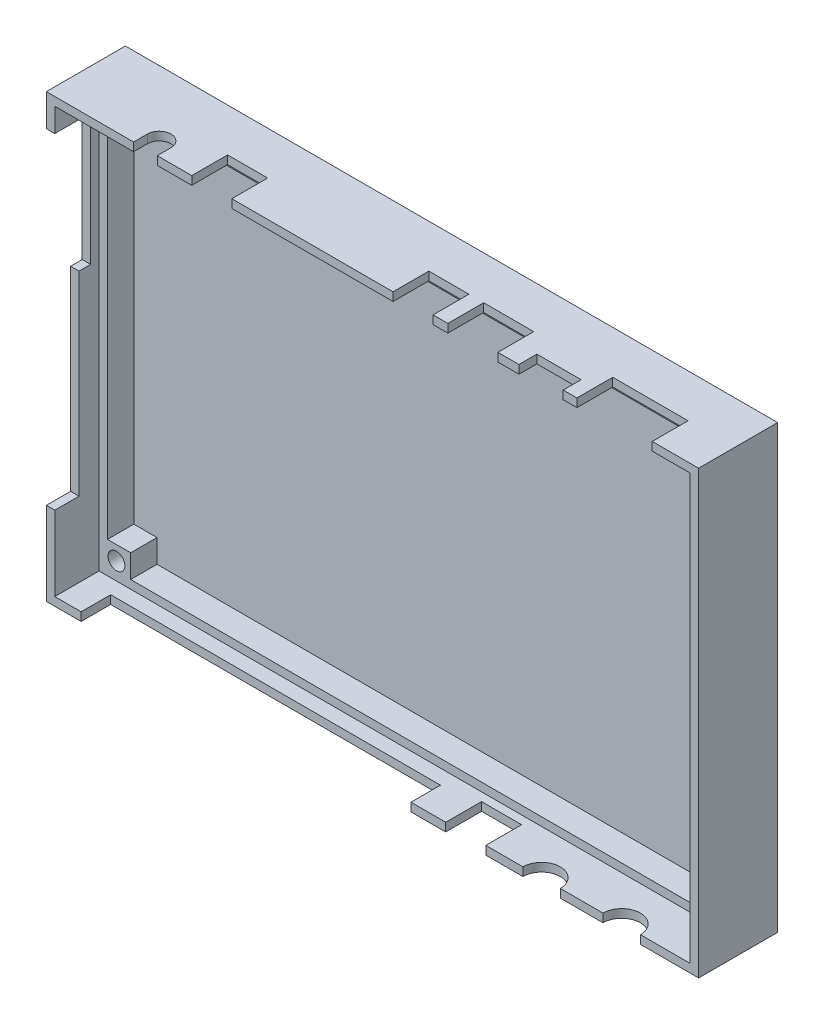
SolidWorks part; units mm, degrees
ref_plane "Front Plane" through (0, 0, 0) normal (0, 0, 1) x (1, 0, 0)
ref_plane "Top Plane" through (0, 0, 0) normal (0, 1, 0) x (1, 0, 0)
ref_plane "Right Plane" through (0, 0, 0) normal (1, 0, 0) x (0, 0, -1)
sketch "Sketch1" plane through (0, 0, 0) normal (0, 0, 1) x (1, 0, 0)
  line L1 (-60.3, 40.3) -> (60.3, 40.3)
  line L2 (-60.3, 40.3) -> (-60.3, -40.3)
  line L3 (-60.3, -40.3) -> (60.3, -40.3)
  line L4 (60.3, 40.3) -> (60.3, -40.3)
  line L5 (-60.3, 40.3) -> (60.3, -40.3) construction
  line L6 (-60.3, -40.3) -> (60.3, 40.3) construction
  point P0 (0, 0)
  dimension "D1" = 80.6
  dimension "D2" = 120.6
extrude "Boss-Extrude1" add sketch "Sketch1" along normal blind 1.6
sketch "Sketch2" plane through (0, 0, 0) normal (0, 0, 1) x (1, 0, 0)
  line L0 (-60.3, 40.3) -> (-60.3, -40.3)
  line L1 (-60.3, -40.3) -> (60.3, -40.3)
  line L2 (60.3, -40.3) -> (60.3, 40.3)
  line L3 (60.3, 40.3) -> (-60.3, 40.3)
  line L4 (-61.9, 41.9) -> (-61.9, -41.9)
  line L5 (-61.9, -41.9) -> (61.9, -41.9)
  line L6 (61.9, -41.9) -> (61.9, 41.9)
  line L7 (61.9, 41.9) -> (-61.9, 41.9)
  dimension "D1" = 1.6
  dimension "D2" = 1.6
  dimension "D3" = 1.6
  dimension "D4" = 1.6
  dimension "D5" = 83.8
  dimension "D6" = 123.8
extrude "Boss-Extrude2" add sketch "Sketch2" along normal blind 8.2
sketch "Sketch3" plane through (0, 0, 1.6) normal (0, 0, 1) x (1, 0, 0)
  line L0 (60.3, -40.3) -> (60.3, 40.3) construction
  line L3 (-58.7, 34.3) -> (-54.3, 34.3)
  line L4 (-54.3, 38.5) -> (-54.3, 34.3)
  line L6 (60.3, 40.3) -> (60.3, -40.3)
  line L7 (58.7, 34.3) -> (54.3, 34.3)
  line L8 (54.3, 38.5) -> (54.3, 34.3)
  line L9 (60.3, -40.3) -> (60.3, 40.3) construction
  line L10 (60.3, 40.3) -> (-60.3, 40.3)
  line L11 (60.3, -40.3) -> (-60.3, -40.3)
  line L13 (58.7, -34.3) -> (54.3, -34.3)
  line L14 (54.3, -38.7) -> (54.3, -34.3)
  line L16 (-60.3, -40.3) -> (-60.3, 40.3)
  line L17 (-58.7, -34.3) -> (-54.3, -34.3)
  line L18 (-54.3, -38.7) -> (-54.3, -34.3)
  line L19 (54.3, 38.5) -> (-54.3, 38.5)
  line L20 (58.7, 34.3) -> (58.7, -34.3)
  line L21 (54.3, -38.7) -> (-54.3, -38.7)
  line L22 (-58.7, -34.3) -> (-58.7, 34.3)
  line L23 (-60.3, -40.3) -> (60.3, -40.3) construction
  line L24 (-60.3, 40.3) -> (-60.3, -40.3) construction
  line L25 (60.3, 40.3) -> (-60.3, 40.3) construction
  line L26 (60.3, 40.3) -> (-60.3, 40.3) construction
  dimension "D1" = 6
  dimension "D2" = 6
  dimension "D3" = 6
  dimension "D4" = 6
  dimension "D6" = 1.6
  dimension "D7" = 1.6
  dimension "D8" = 1.6
extrude "Boss-Extrude3" add sketch "Sketch3" along normal blind 5
sketch "Sketch4" plane through (0, 0, 6.6) normal (0, 0, 1) x (1, 0, 0)
  circle A0 centre (-57, 37) radius 1.6
  circle A1 centre (57, 37) radius 1.6
  circle A2 centre (57, -37) radius 1.6
  circle A3 centre (-57, -37) radius 1.6
  dimension "D3" = 3.2
  dimension "D1" = 57
  dimension "D2" = 37
  dimension "D4" = 74
  dimension "D5" = 114
  dimension "D6" = 74
  dimension "D7" = 114
extrude "Cut-Extrude1" cut sketch "Sketch4" against normal blind 5
sketch "Sketch5" plane through (0, 0, 8.2) normal (0, 0, 1) x (1, 0, 0)
  line L0 (-60.3, -40.3) -> (60.3, -40.3) construction
  line L1 (61.9, -41.9) -> (21.5, -41.9)
  line L2 (61.9, -41.9) -> (61.9, -40.3)
  line L3 (61.9, -40.3) -> (21.5, -40.3)
  line L4 (21.5, -41.9) -> (21.5, -40.3)
  line L5 (-61.9, -41.9) -> (61.9, -41.9) construction
  line L6 (13.9, -40.3) -> (7.3, -40.3)
  line L7 (13.9, -40.3) -> (13.9, -41.9)
  line L8 (13.9, -41.9) -> (7.3, -41.9)
  line L9 (7.3, -40.3) -> (7.3, -41.9)
  dimension "D1" = 38.8
  dimension "D2" = 46.4
  dimension "D3" = 53
  dimension "D4" = 7.6
extrude "Boss-Extrude4" add sketch "Sketch5" along normal blind 6.8
sketch "Sketch6" plane through (0, -41.9, 0) normal (0, -1, 0) x (1, 0, 0)
  line L0 (21.5, 15) -> (61.9, 15) construction
  circle A0 centre (32.1, 15) radius 3.55
  circle A1 centre (47.3, 15) radius 3.55
  dimension "D1" = 7.1
  dimension "D2" = 15.2
  dimension "D3" = 14.6
extrude "Cut-Extrude2" cut sketch "Sketch6" against normal blind 6.8
sketch "Sketch7" plane through (0, 0, 8.2) normal (0, 0, 1) x (1, 0, 0)
  line L0 (-61.9, -26.1) -> (-61.9, -41.9)
  line L1 (-61.9, 41.9) -> (-61.9, -41.9) construction
  line L2 (-61.9, -41.9) -> (7.3, -41.9) construction
  line L3 (-61.9, -41.9) -> (-55.3, -41.9)
  line L4 (-55.3, -41.9) -> (-55.3, -40.3)
  line L5 (-60.3, -40.3) -> (7.3, -40.3) construction
  line L6 (-55.3, -40.3) -> (-60.3, -40.3)
  line L7 (-60.3, -40.3) -> (-60.3, -26.1)
  line L8 (-60.3, 40.3) -> (-60.3, -40.3) construction
  line L9 (-60.3, -26.1) -> (-61.9, -26.1)
  dimension "D1" = 5
  dimension "D2" = 14.2
extrude "Boss-Extrude5" add sketch "Sketch7" along normal blind 6.8
sketch "Sketch14" plane through (0, 0, 8.2) normal (0, 0, 1) x (1, 0, 0)
  line L1 (-55.3, -40.3) -> (7.3, -40.3)
  line L2 (-55.3, -40.3) -> (-55.3, -41.9)
  line L3 (-55.3, -41.9) -> (7.3, -41.9)
  line L4 (7.3, -40.3) -> (7.3, -41.9)
sketch "Sketch8" plane through (0, 0, 8.2) normal (0, 0, 1) x (1, 0, 0)
  line L0 (-60.3, 40.3) -> (-60.3, -26.1) construction
  line L1 (-61.9, -26.1) -> (-60.3, -26.1)
  line L2 (-61.9, -26.1) -> (-61.9, 10.9)
  line L3 (-61.9, 10.9) -> (-60.3, 10.9)
  line L4 (-60.3, -26.1) -> (-60.3, 10.9)
  dimension "D1" = 37
extrude "Boss-Extrude6" add sketch "Sketch8" along normal blind 2.2
sketch "Sketch9" plane through (0, 0, 8.2) normal (0, 0, 1) x (1, 0, 0)
  line L0 (-60.3, 35.8) -> (-61.9, 35.8)
  line L1 (-60.3, 40.3) -> (-60.3, -40.3) construction
  line L2 (-61.9, 41.9) -> (-61.9, 10.9) construction
  line L3 (-61.9, 35.8) -> (-61.9, 41.9)
  line L4 (-61.9, 41.9) -> (-34.3, 41.9)
  line L5 (61.9, 41.9) -> (-61.9, 41.9) construction
  line L6 (-34.3, 41.9) -> (-34.3, 40.3)
  line L7 (60.3, 40.3) -> (-60.3, 40.3) construction
  line L8 (-34.3, 40.3) -> (-60.3, 40.3)
  line L9 (-60.3, 40.3) -> (-60.3, 35.8)
  line L10 (-26.7, 41.9) -> (-26.7, 40.3)
  line L11 (60.3, 40.3) -> (-60.3, 40.3) construction
  line L12 (-26.7, 40.3) -> (3.9, 40.3)
  line L13 (3.9, 40.3) -> (3.9, 41.9)
  line L14 (3.9, 41.9) -> (-26.7, 41.9)
  line L16 (11.5, 41.9) -> (14.3, 41.9)
  line L17 (11.5, 41.9) -> (11.5, 40.3)
  line L18 (11.5, 40.3) -> (14.3, 40.3)
  line L19 (14.3, 41.9) -> (14.3, 40.3)
  dimension "D1" = 4.5
  dimension "D2" = 26
  dimension "D3" = 33.6
  dimension "D4" = 64.2
  dimension "D5" = 71.8
  dimension "D6" = 2.8
  dimension "D7" = 7.6
  dimension "D8" = 7.6
extrude "Boss-Extrude7" add sketch "Sketch9" along normal blind 6.8
sketch "Sketch10" plane through (0, 41.9, 0) normal (0, 1, 0) x (1, 0, 0)
  line L0 (-45.35, -12.4) -> (-45.35, -15)
  line L1 (-34.3, -15) -> (-61.9, -15) construction
  line L2 (-45.35, -15) -> (-40.85, -15)
  line L3 (-40.85, -15) -> (-40.85, -12.4)
  arc A0 (-40.85, -12.4) -> (-45.35, -12.4) centre (-43.1, -12.4) ccw
  dimension "D1" = 4.5
  dimension "D2" = 2.6
  dimension "D3" = 18.8
extrude "Cut-Extrude3" cut sketch "Sketch10" against normal blind 6.8
sketch "Sketch11" plane through (0, 0, 8.2) normal (0, 0, 1) x (1, 0, 0)
  line L0 (61.9, 41.9) -> (14.3, 41.9) construction
  line L1 (23.8, 41.9) -> (38.8, 41.9)
  line L2 (23.8, 41.9) -> (23.8, 40.3)
  line L3 (23.8, 40.3) -> (38.8, 40.3)
  line L4 (38.8, 41.9) -> (38.8, 40.3)
  line L5 (60.3, 40.3) -> (-60.3, 40.3) construction
  dimension "D1" = 21.5
  dimension "D2" = 36.5
extrude "Boss-Extrude8" add sketch "Sketch11" along normal blind 6.8
sketch "Sketch12" plane through (0, 41.9, 0) normal (0, 1, 0) x (1, 0, 0)
  line L0 (38.8, -15) -> (23.8, -15) construction
  line L1 (27.8, -15) -> (36.2, -15)
  line L2 (27.8, -15) -> (27.8, -11.6)
  line L3 (27.8, -11.6) -> (36.2, -11.6)
  line L4 (36.2, -15) -> (36.2, -11.6)
  dimension "D1" = 3.4
  dimension "D2" = 2.6
  dimension "D3" = 11
extrude "Cut-Extrude4" cut sketch "Sketch12" against normal blind 6.8
sketch "Sketch13" plane through (0, 0, 8.2) normal (0, 0, 1) x (1, 0, 0)
  line L0 (61.9, -40.3) -> (60.3, -40.3)
  line L1 (60.3, -40.3) -> (60.3, 40.3)
  line L2 (60.3, 40.3) -> (53.1, 40.3)
  line L3 (60.3, 40.3) -> (38.8, 40.3) construction
  line L4 (53.1, 40.3) -> (53.1, 41.9)
  line L5 (61.9, 41.9) -> (38.8, 41.9) construction
  line L6 (53.1, 41.9) -> (61.9, 41.9)
  line L7 (61.9, 41.9) -> (61.9, -40.3)
  dimension "D1" = 7.2
extrude "Boss-Extrude9" add sketch "Sketch13" along normal blind 6.8
extrude "Boss-Extrude10" add sketch "Sketch14" along normal blind 1.2
equation "\"D3@Sketch6\"=13.00+1.6mm"
